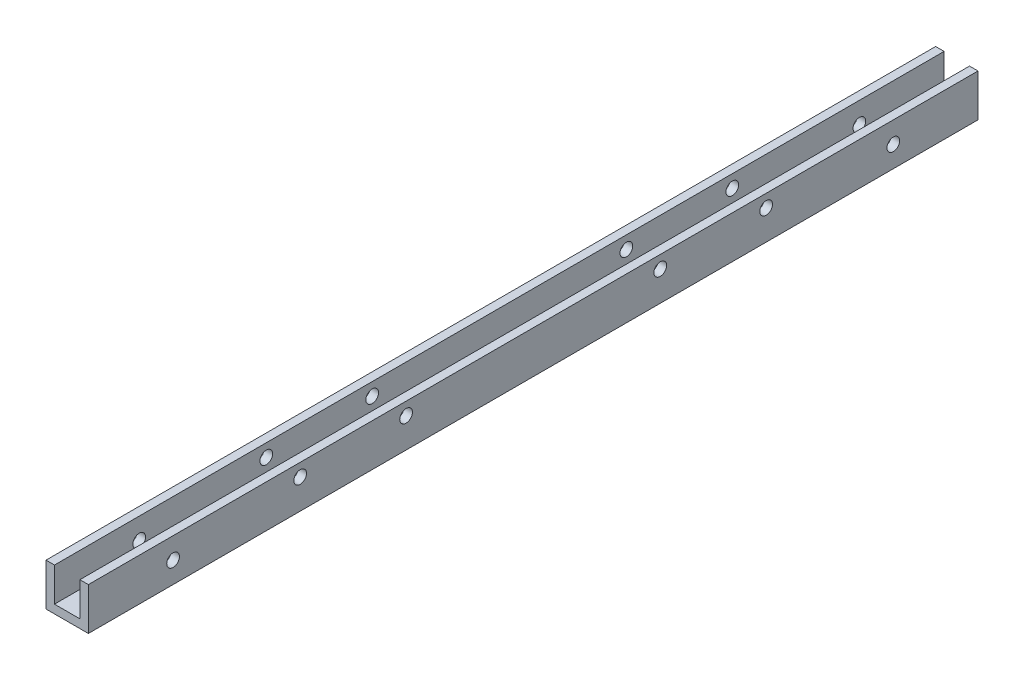
SolidWorks part; units mm, degrees
ref_plane "前视基准面" through (0, 0, 0) normal (0, 0, 1) x (1, 0, 0)
ref_plane "上视基准面" through (0, 0, 0) normal (0, 1, 0) x (1, 0, 0)
ref_plane "右视基准面" through (0, 0, 0) normal (1, 0, 0) x (0, 0, -1)
sketch "草图1" plane through (0, 0, 0) normal (0, 0, 1) x (1, 0, 0)
  line L0 (2.5217, 3.6739) -> (4.5217, 3.6739)
  line L1 (-5.4783, 3.6739) -> (-3.4783, 3.6739)
  line L2 (-5.4783, 3.6739) -> (-5.4783, -6.3261)
  line L3 (-5.4783, -6.3261) -> (4.5217, -6.3261)
  line L4 (4.5217, 3.6739) -> (4.5217, -6.3261)
  line L6 (-3.4783, 3.6739) -> (-3.4783, -4.3261)
  line L7 (-3.4783, -4.3261) -> (2.5217, -4.3261)
  line L8 (2.5217, 3.6739) -> (2.5217, -4.3261)
  dimension "D1" = 10
  dimension "D2" = 10
  dimension "D3" = 8
  dimension "D4" = 6
  dimension "D5" = 2
extrude "凸台-拉伸1" add sketch "草图1" along normal blind 210
sketch "草图2" plane through (4.5217, 0, 0) normal (1, 0, 0) x (0, 0, -1)
  line L0 (-210, 3.6739) -> (0, 3.6739) construction
  circle A0 centre (-160, 0.6739) radius 1.5
  circle A1 centre (-135, 0.6739) radius 1.5
  circle A2 centre (-75, 0.6739) radius 1.5
  circle A3 centre (-50, 0.6739) radius 1.5
  point P10 (-105, 3.6739)
  point P11 (0, 0)
  dimension "D1" = 110
  dimension "D9" = 3
  dimension "D2" = 60
  dimension "D3" = 30
  dimension "D4" = 55
  dimension "D5" = 3
  dimension "D6" = 3
  dimension "D7" = 3
  dimension "D8" = 3
extrude "切除-拉伸1" cut sketch "草图2" against normal blind 10
sketch "草图3" plane through (4.5217, 0, 0) normal (1, 0, 0) x (0, 0, -1)
  line L0 (-210, -6.3261) -> (0, -6.3261) construction
  line L1 (0, -6.3261) -> (0, 3.6739) construction
  line L2 (-210, -6.3261) -> (-210, 3.6739) construction
  circle A0 centre (-20, -1.3261) radius 1.5
  circle A1 centre (-190, -1.3261) radius 1.5
  dimension "D1" = 5
  dimension "D3" = 20
  dimension "D2" = 20
  dimension "D4" = 5
extrude "切除-拉伸2" cut sketch "草图3" against normal blind 10
sketch "草图5" plane through (0, -6.3261, 0) normal (0, -1, 0) x (1, 0, 0)
  line L0 (4.5217, 210) -> (4.5217, 0) construction
  line L1 (-5.4783, 210) -> (4.5217, 210) construction
  circle A0 centre (-0.4783, 105) radius 2.5
  dimension "D1" = 5
  dimension "D2" = 105
extrude "切除-拉伸3" cut sketch "草图5" against normal blind 10
